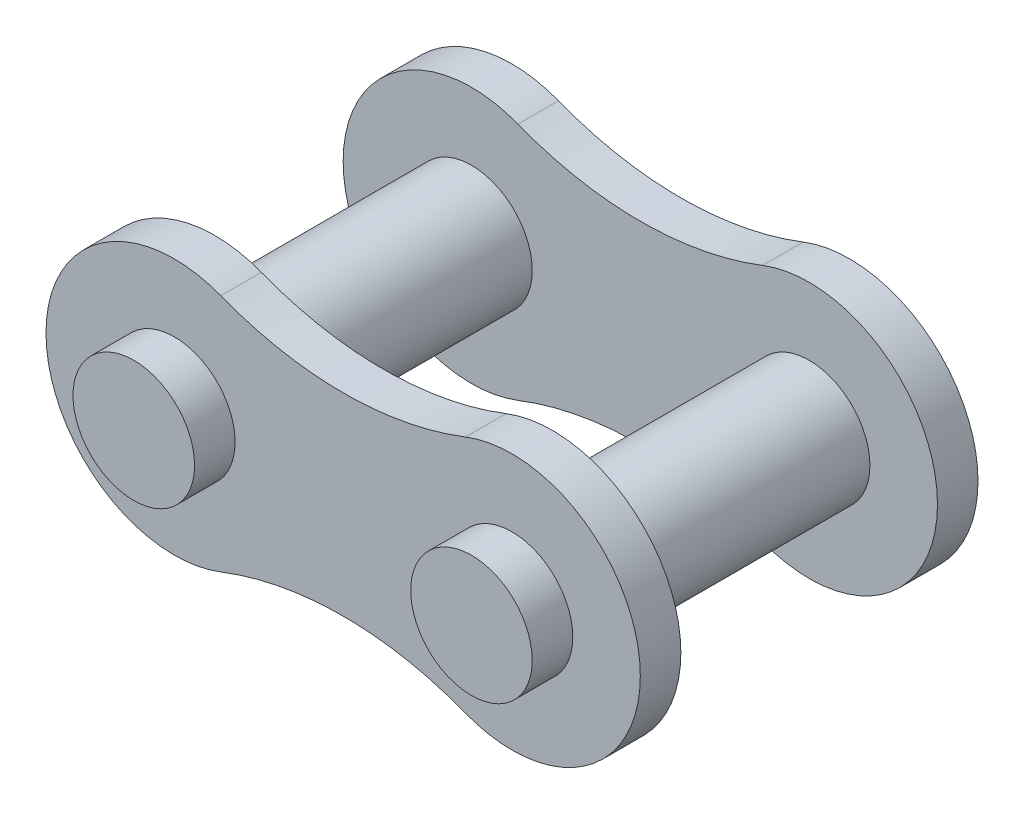
SolidWorks part; units mm, degrees
material "Rubber"
ref_plane "Front" through (0, 0, 0) normal (0, 0, 1) x (1, 0, 0)
ref_plane "Top" through (0, 0, 0) normal (0, 1, 0) x (1, 0, 0)
ref_plane "Right" through (0, 0, 0) normal (1, 0, 0) x (0, 0, -1)
sketch "Sketch4" plane through (0, 0, 0) normal (0, 0, 1) x (1, 0, 0)
  arc A0 (-7.2243, -2.249) -> (-7.2243, 2.249) centre (-6.35, 0) ccw
  arc A1 (-11.8257, 2.249) -> (-11.8257, -2.249) centre (-12.7, 0) ccw
  arc A2 (-7.2243, -2.249) -> (-11.8257, -2.249) centre (-9.525, -8.1676) ccw
  arc A3 (-11.8257, 2.249) -> (-7.2243, 2.249) centre (-9.525, 8.1676) ccw
  circle A4 centre (-12.7, 0) radius 1.143
  circle A5 centre (-6.35, 0) radius 1.143
  dimension "D1" = 6.35
extrude "outer link 1" add sketch "Sketch4" against normal blind 0.762 from offset 3.175 separate body
mirror "outer link 2" about plane through (0, 0, 0) normal (0, 0, 1) of bodies 107
sketch "Sketch5" plane through (0, 0, 0) normal (0, 0, 1) x (1, 0, 0)
  circle A0 centre (-12.7, 0) radius 1.143
  circle A2 centre (-6.35, 0) radius 1.143
  circle A3 centre (-6.35, 0) radius 1.143 construction
extrude "pins" add sketch "Sketch5" along normal mid plane 7.874
